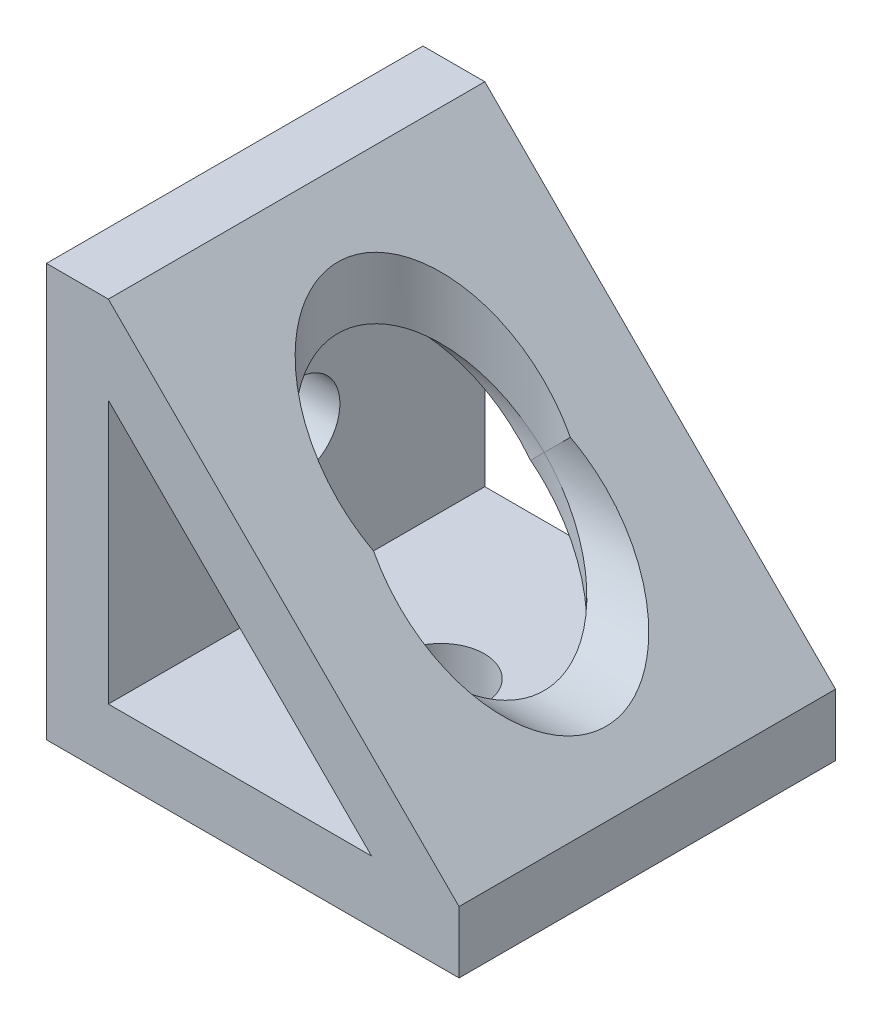
SolidWorks part; units mm, degrees
ref_plane "Front Plane" through (0, 0, 0) normal (0, 0, 1) x (1, 0, 0)
ref_plane "Top Plane" through (0, 0, 0) normal (0, 1, 0) x (1, 0, 0)
ref_plane "Right Plane" through (0, 0, 0) normal (1, 0, 0) x (0, 0, -1)
sketch "Sketch1" plane through (0, 0, 0) normal (0, 0, 1) x (1, 0, 0)
  line L0 (0, 20) -> (0, -20) construction
  line L1 (20, 0) -> (-20, 0) construction
  line L2 (-4.2, -20) -> (4.2, -20) construction
  line L3 (-20, -20) -> (-20, -14) construction
  line L4 (-10, -14) -> (10, -14) construction
  point P4 (0, 0)
  point P8 (0, 0)
  point P11 (0, -20)
  point P16 (0, -14)
  dimension "Length" = 40
  dimension "Clearance Hole" = 8.4
  dimension "Wall" = 6
  dimension "Access Hole" = 20
  dimension "For Rail Height" = 40
sketch "Sketch3" plane through (0, 0, 0) normal (1, 0, 0) x (0, 0, -1)
  line L0 (18.25, 0) -> (-18.25, 0) construction
  point P3 (0, 0)
  dimension "Thickness" = 36.5
sketch "Sketch2" plane through (0, 0, 0) normal (0, 0, 1) x (1, 0, 0)
  line L0 (-20, 20) -> (-20, -20)
  line L1 (-20, -20) -> (20, -20)
  line L3 (-4.2, -20) -> (4.2, -20) construction
  line L4 (-20, -20) -> (-20, -14) construction
  line L5 (20, -20) -> (20, -14)
  line L6 (20, -14) -> (-14, 20)
  line L7 (-14, 20) -> (-20, 20)
  line L8 (-14, 11.5147) -> (-14, -14)
  line L9 (-14, -14) -> (11.5147, -14)
  line L10 (11.5147, -14) -> (11.5147, -14)
  line L11 (11.5147, -14) -> (-14, 11.5147)
  line L12 (-14, 11.5147) -> (-14, 11.5147)
extrude "Boss-Extrude1" add sketch "Sketch2" against normal up to vertex (18.25 mm away) and the other way up to vertex (18.25 mm away) up to point (0, 0, -18.25) other way up to point (0, 0, 18.25)
sketch "Sketch4" plane through (0, -20, 0) normal (0, -1, 0) x (1, 0, 0)
  line L0 (-4.2, 0) -> (4.2, 0) construction
  line L1 (-4.2, 0) -> (4.2, 0) construction
  circle A0 centre (0, 0) radius 4.2
extrude "Cut-Extrude1" cut sketch "Sketch4" against normal up to next
sketch "Sketch6" plane through (0, -14, 0) normal (0, 1, 0) x (1, 0, 0)
  circle A0 centre (0, 0) radius 10
extrude "Cut-Extrude2" cut sketch "Sketch6" along normal through all
ref_plane "Plane1" through (0, 0, 0) normal (0.7071, -0.7071, 0) x (-0.7071, -0.7071, 0)
mirror "Mirror1" about plane through (0, 0, 0) normal (0.7071, -0.7071, 0) of "Cut-Extrude2", "Cut-Extrude1"
sketch "Sketch7" plane through (0, -14, 0) normal (0, 1, 0) x (1, 0, 0)
  line L0 (0, 0) -> (3.6373, 2.1) construction
  line L1 (20, -18.25) -> (-14, -18.25) construction
  circle A0 centre (0, 0) radius 4.2 construction
  dimension "D1" = 30
sketch "Sketch8" plane through (-14, 0, 0) normal (1, 0, 0) x (0, 0, -1)
  line L0 (0, 0) -> (-2.9698, 2.9698) construction
  line L1 (18.25, -20) -> (-18.25, -20) construction
  circle A0 centre (0, 0) radius 4.2 construction
  dimension "D1" = 45
